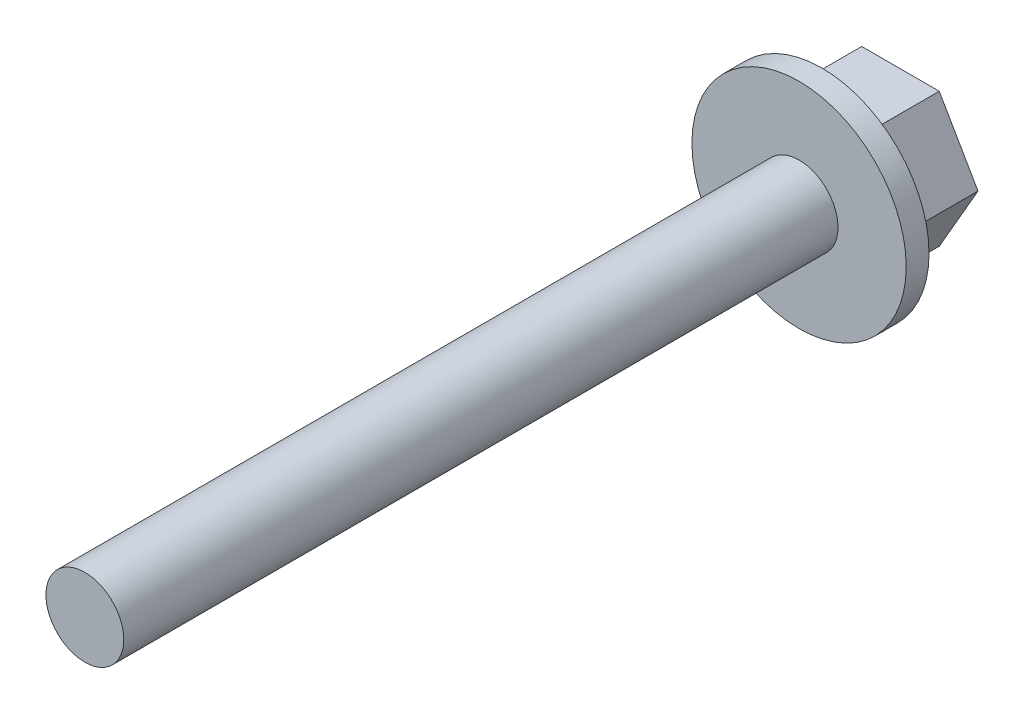
SolidWorks part; units mm, degrees
material "Ti-6Al-4VSolution treated and aged (SS)"
ref_plane "Front Plane" through (0, 0, 0) normal (0, 0, 1) x (1, 0, 0)
ref_plane "Top Plane" through (0, 0, 0) normal (0, 1, 0) x (1, 0, 0)
ref_plane "Right Plane" through (0, 0, 0) normal (1, 0, 0) x (0, 0, -1)
sketch "Sketch1" plane through (0, 0, 0) normal (0, 0, 1) x (1, 0, 0)
  line L1 (2.757, 0) -> (1.3785, 2.3876)
  line L2 (1.3785, 2.3876) -> (-1.3785, 2.3876)
  line L3 (-1.3785, 2.3876) -> (-2.757, 0)
  line L4 (-2.757, 0) -> (-1.3785, -2.3876)
  line L5 (-1.3785, -2.3876) -> (1.3785, -2.3876)
  line L6 (1.3785, -2.3876) -> (2.757, 0)
  circle A0 centre (0, 0) radius 2.3876 construction
  dimension "D1" = 4.7752
extrude "Boss-Extrude1" add sketch "Sketch1" along normal blind 2.794
sketch "Sketch2" plane through (0, 0, 2.794) normal (0, 0, 1) x (1, 0, 0)
  circle A0 centre (0, 0) radius 3.81
  dimension "D1" = 7.62
extrude "Boss-Extrude2" add sketch "Sketch2" along normal blind 0.8128
sketch "Sketch3" plane through (0, 0, 3.6068) normal (0, 0, 1) x (1, 0, 0)
  circle A0 centre (0, 0) radius 1.3843
  dimension "D1" = 2.7686
extrude "Boss-Extrude3" add sketch "Sketch3" along normal blind 25.4
fillet "Fillet1" [suppressed] radius 0.1016
sketch "Sketch4" plane through (0, 0, 29.0068) normal (0, 0, 1) x (1, 0, 0)
  circle A0 centre (0, 0) radius 1.25
  dimension "D1" = 2.5
equation "\"ShankLength\"= 1.00in'Max of 1.00 in, can be sized down"
equation "\"ThreadLength\"= .073in'Min of 0.073 in, can be sized up"
